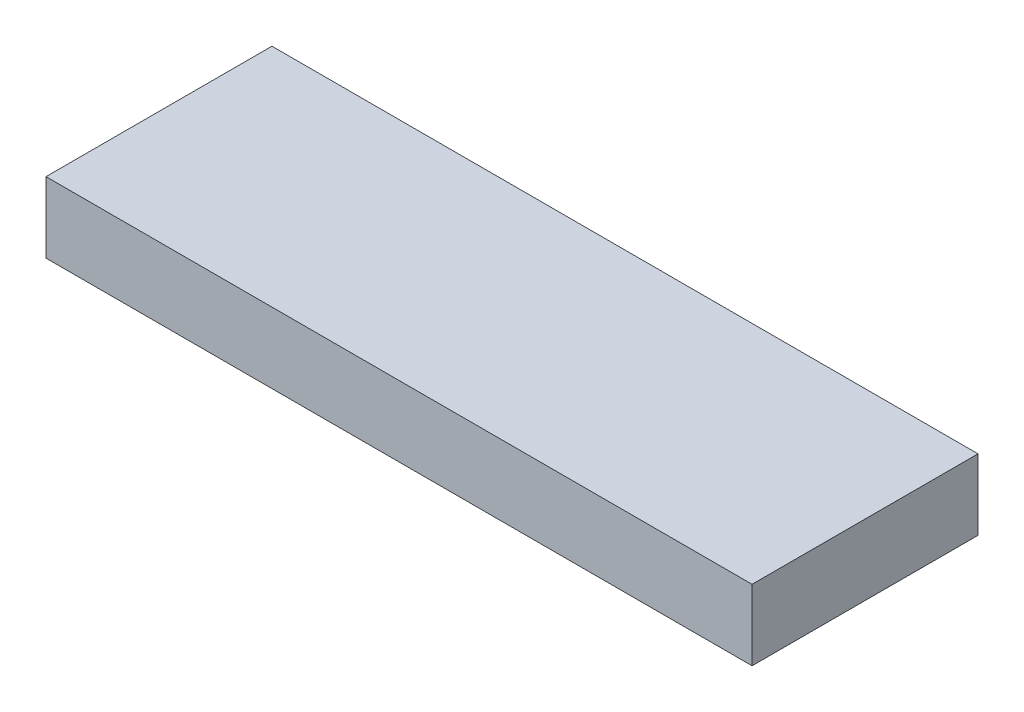
SolidWorks part; units mm, degrees
ref_plane "Front Plane" through (0, 0, 0) normal (0, 0, 1) x (1, 0, 0)
ref_plane "Top Plane" through (0, 0, 0) normal (0, 1, 0) x (1, 0, 0)
ref_plane "Right Plane" through (0, 0, 0) normal (1, 0, 0) x (0, 0, -1)
sketch "Sketch1" plane through (0, 0, 0) normal (0, 1, 0) x (1, 0, 0)
  line L1 (0, 0) -> (25, 0)
  line L2 (0, 0) -> (0, 8)
  line L3 (0, 8) -> (25, 8)
  line L4 (25, 0) -> (25, 8)
  dimension "D1" = 25
  dimension "D2" = 8
extrude "Boss-Extrude1" add sketch "Sketch1" along normal blind 2.5
